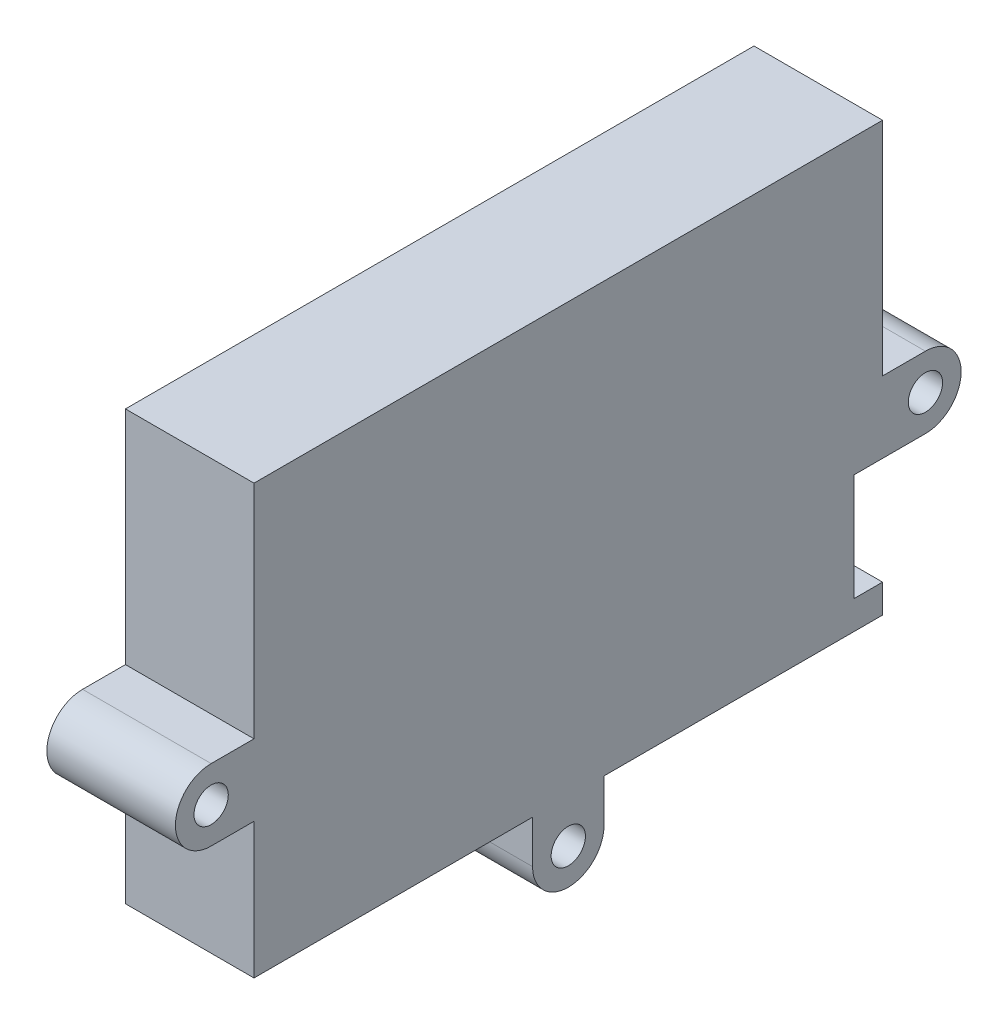
SolidWorks part; units mm, degrees
ref_plane "Front Plane" through (0, 0, 0) normal (0, 0, 1) x (1, 0, 0)
ref_plane "Top Plane" through (0, 0, 0) normal (0, 1, 0) x (1, 0, 0)
ref_plane "Right Plane" through (0, 0, 0) normal (1, 0, 0) x (0, 0, -1)
sketch "Sketch1" plane through (0, 0, 0) normal (1, 0, 0) x (0, 0, -1)
  line L1 (0, 0) -> (50.8, 0)
  line L2 (0, 0) -> (0, 33.02)
  line L3 (0, 33.02) -> (50.8, 33.02)
  line L4 (50.8, 0) -> (50.8, 33.02)
  dimension "D1" = 33.02
  dimension "D2" = 50.8
extrude "Boss-Extrude1" add sketch "Sketch1" along normal blind 2.54
sketch "Sketch2" plane through (2.54, 0, 0) normal (1, 0, 0) x (0, 0, -1)
  line L0 (57.15, 9.525) -> (50.8, 9.525)
  line L1 (50.8, 0) -> (50.8, 33.02) construction
  line L2 (57.15, 15.875) -> (50.8, 15.875)
  line L3 (-6.35, 9.525) -> (0, 9.525)
  line L4 (28.575, -6.35) -> (28.575, 0)
  line L5 (0, 0) -> (50.8, 0) construction
  line L6 (0, 33.02) -> (0, 0) construction
  line L7 (22.225, -6.35) -> (22.225, 0)
  line L8 (-6.35, 15.875) -> (0, 15.875)
  circle A0 centre (57.15, 12.7) radius 1.524
  circle A1 centre (57.15, 12.7) radius 3.175
  circle A2 centre (25.4, -6.35) radius 1.524
  circle A3 centre (25.4, -6.35) radius 3.175
  circle A4 centre (-6.35, 12.7) radius 1.524
  circle A5 centre (-6.35, 12.7) radius 3.175
  line M2 (0, 33.02) -> (0, 0)
  line M3 (0, 0) -> (50.8, 0)
  line M4 (50.8, 0) -> (50.8, 33.02)
  dimension "D1" = 6.35
  dimension "D2" = 6.35
  dimension "D3" = 6.35
  dimension "D5" = 6.35
  dimension "D7" = 3.048
  dimension "D8" = 3.048
  dimension "D9" = 3.048
  dimension "D4" = 9.525
  dimension "D6" = 22.225
extrude "Boss-Extrude3" add sketch "Sketch2" against normal blind 2.54 contours A5 L3 L8 M2 | A5 A4 | A3 L4 L7 M3 | A3 A2 | A1 L2 L0 M4 | A1 A0
sketch "Sketch3" plane through (2.54, 0, 0) normal (1, 0, 0) x (0, 0, -1)
  line L0 (50.8, 0) -> (50.8, 9.525) construction
  line L1 (0, 33.02) -> (-2.54, 33.02)
  line L2 (0, 33.02) -> (0, 0)
  line L3 (0, 0) -> (-2.54, 0)
  line L4 (-2.54, 33.02) -> (-2.54, 0)
  line L5 (-2.54, 0) -> (50.8, 0)
  line L6 (-2.54, 0) -> (-2.54, -2.54)
  line L7 (-2.54, -2.54) -> (50.8, -2.54)
  line L8 (50.8, 0) -> (50.8, -2.54)
  line L9 (50.8, -2.54) -> (53.34, -2.54)
  line L10 (50.8, -2.54) -> (50.8, 33.02)
  line L11 (50.8, 33.02) -> (53.34, 33.02)
  line L12 (53.34, -2.54) -> (53.34, 33.02)
  line L13 (50.8, 33.02) -> (0, 33.02) construction
  line L15 (-2.54, 33.02) -> (53.34, 33.02)
  line L16 (-2.54, 33.02) -> (-2.54, 35.56)
  line L17 (-2.54, 35.56) -> (53.34, 35.56)
  line L18 (53.34, 33.02) -> (53.34, 35.56)
  line M11 (0, 33.02) -> (0, 15.875)
  line M12 (0, 15.875) -> (-6.35, 15.875)
  line M14 (-6.35, 9.525) -> (0, 9.525)
  line M15 (0, 9.525) -> (0, 0)
  line M16 (0, 0) -> (22.225, 0)
  line M17 (22.225, 0) -> (22.225, -6.35)
  line M19 (28.575, -6.35) -> (28.575, 0)
  line M20 (28.575, 0) -> (50.8, 0)
  line M21 (50.8, 0) -> (50.8, 9.525)
  line M22 (50.8, 9.525) -> (57.15, 9.525)
  line M24 (57.15, 15.875) -> (50.8, 15.875)
  line M25 (50.8, 15.875) -> (50.8, 33.02)
  line M26 (50.8, 33.02) -> (0, 33.02)
  dimension "D1" = 2.54
  dimension "D2" = 2.54
  dimension "D3" = 2.54
  dimension "D4" = 2.54
extrude "Boss-Extrude4" add sketch "Sketch3" against normal blind 11.43 contours L8 L7 M20 M19 | L6 L7 L3 M17 M16 | L7 L5 M17 M19 | L9 L12 L8 M22 M21 | L12 L10 M22 M24 | L12 L11 M24 M25 | L11 L18 L17 L16 L1 M26 | L1 L4 M12 M11 | L4 L2 M12 M14 | L4 L3 M14 M15
sketch "Sketch5" plane through (-8.89, 0, 0) normal (-1, 0, 0) x (0, 0, 1)
  line L1 (-50.8, 0) -> (-53.34, 0)
  line L2 (-50.8, 0) -> (-50.8, 9.525)
  line L3 (-50.8, 9.525) -> (-53.34, 9.525)
  line L4 (-53.34, 0) -> (-53.34, 9.525)
extrude "Cut-Extrude2" cut sketch "Sketch5" against normal blind 11.43
sketch "Sketch6" plane through (0, 0, 0) normal (-1, 0, 0) x (0, 0, 1)
  line L0 (2.54, 15.875) -> (2.54, 9.525) construction
  line L1 (2.54, 9.525) -> (6.35, 9.525) construction
  line L2 (6.35, 15.875) -> (2.54, 15.875) construction
  line L3 (-22.225, -2.54) -> (-28.575, -2.54) construction
  line L4 (-28.575, -2.54) -> (-28.575, -6.35) construction
  line L5 (-22.225, -6.35) -> (-22.225, -2.54) construction
  line L6 (-53.34, 15.875) -> (-53.34, 9.525) construction
  line L7 (-57.15, 15.875) -> (-53.34, 15.875) construction
  line L8 (-57.15, 9.525) -> (-53.34, 9.525) construction
  line L9 (2.54, 15.875) -> (2.54, 9.525)
  line L10 (2.54, 9.525) -> (6.35, 9.525)
  line L11 (6.35, 15.875) -> (2.54, 15.875)
  line L12 (-22.225, -2.54) -> (-28.575, -2.54)
  line L13 (-28.575, -2.54) -> (-28.575, -6.35)
  line L14 (-22.225, -6.35) -> (-22.225, -2.54)
  line L15 (-53.34, 15.875) -> (-53.34, 9.525)
  line L16 (-57.15, 15.875) -> (-53.34, 15.875)
  line L17 (-57.15, 9.525) -> (-53.34, 9.525)
  arc A0 (6.35, 9.525) -> (6.35, 15.875) centre (6.35, 12.7) ccw construction
  arc A1 (-28.575, -6.35) -> (-22.225, -6.35) centre (-25.4, -6.35) ccw construction
  circle A2 centre (-57.15, 12.7) radius 1.524 construction
  arc A3 (-57.15, 15.875) -> (-57.15, 9.525) centre (-57.15, 12.7) ccw construction
  arc A4 (6.35, 9.525) -> (6.35, 15.875) centre (6.35, 12.7) ccw
  arc A5 (-28.575, -6.35) -> (-22.225, -6.35) centre (-25.4, -6.35) ccw
  circle A6 centre (-57.15, 12.7) radius 1.524
  arc A7 (-57.15, 15.875) -> (-57.15, 9.525) centre (-57.15, 12.7) ccw
  circle A8 centre (-25.4, -6.35) radius 1.524
  circle A9 centre (6.35, 12.7) radius 1.524
  dimension "D1" = 3.048
  dimension "D2" = 3.048
extrude "Boss-Extrude7" add sketch "Sketch6" along normal up to surface (8.89 mm away) up to face at (-8.89, 15.113, -30.988)
